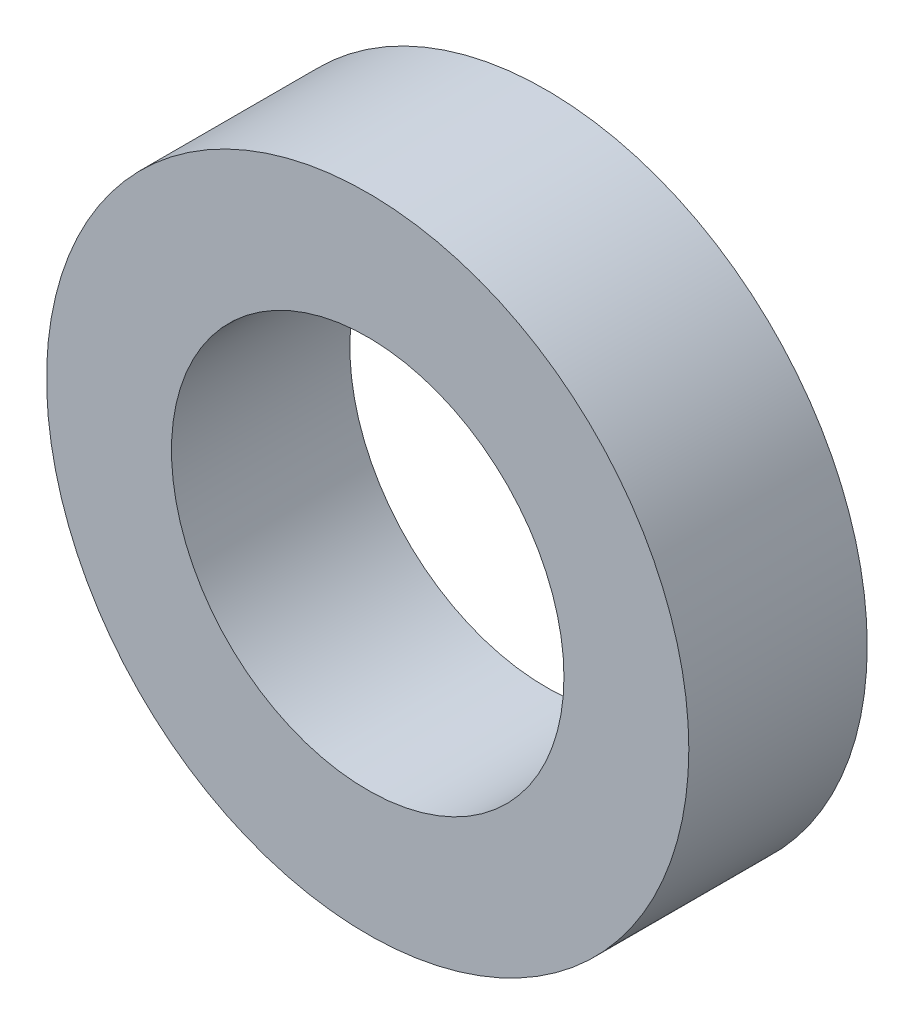
SolidWorks part; units mm, degrees
ref_plane "前视基准面" through (0, 0, 0) normal (0, 0, 1) x (1, 0, 0)
ref_plane "上视基准面" through (0, 0, 0) normal (0, 1, 0) x (1, 0, 0)
ref_plane "右视基准面" through (0, 0, 0) normal (1, 0, 0) x (0, 0, -1)
sketch "草图1" plane through (0, 0, 0) normal (0, 0, 1) x (1, 0, 0)
  circle A0 centre (0, 0) radius 27.5
  circle A1 centre (0, 0) radius 45
  dimension "D1" = 55
  dimension "D2" = 90
extrude "凸台-拉伸1" add sketch "草图1" along normal blind 25
